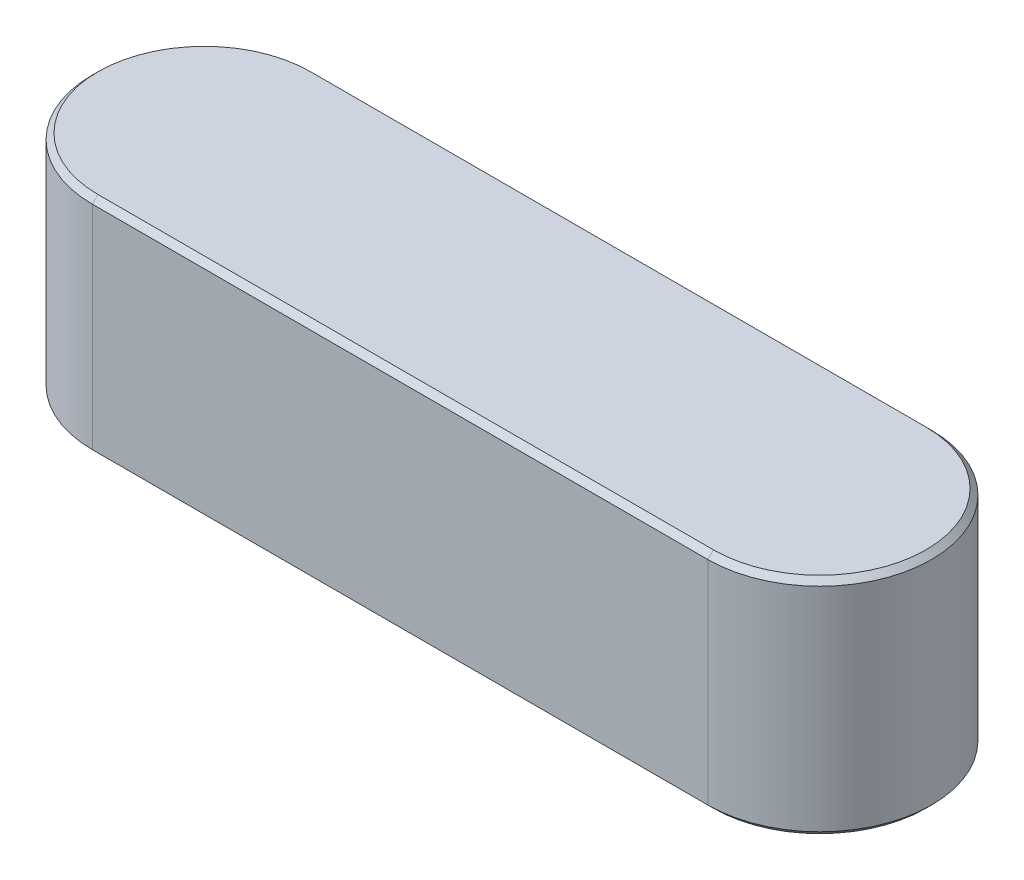
SolidWorks part; units mm, degrees
material "Alliage 1060"
ref_plane "Plan de face" through (0, 0, 0) normal (0, 0, 1) x (1, 0, 0)
ref_plane "Plan de dessus" through (0, 0, 0) normal (0, 1, 0) x (1, 0, 0)
ref_plane "Plan de droite" through (0, 0, 0) normal (1, 0, 0) x (0, 0, -1)
sketch "Esquisse1" plane through (0, 0, 0) normal (0, 1, 0) x (1, 0, 0)
  line L0 (-13.7731, 0) -> (12.8025, 0) construction
  line L1 (-5.5, 0) -> (5.5, 0) construction
  line L2 (-5.5, 2) -> (5.5, 2)
  line L3 (-5.5, -2) -> (5.5, -2)
  arc A0 (-5.5, 2) -> (-5.5, -2) centre (-5.5, 0) ccw
  arc A1 (5.5, -2) -> (5.5, 2) centre (5.5, 0) ccw
  point P5 (0, 0)
  dimension "D1" = 11
  dimension "D2" = 4
extrude "Boss.-Extru.1" add sketch "Esquisse1" along normal blind 4
chamfer "Chanfrein1" distance 0.1 angle 45 8 edges at (0, 0, 2) (7.5, 0, 0) (0, 0, -2) (-7.5, 0, 0) (0, 4, -2) (7.5, 4, 0) (0, 4, 2) (-7.5, 4, 0)
